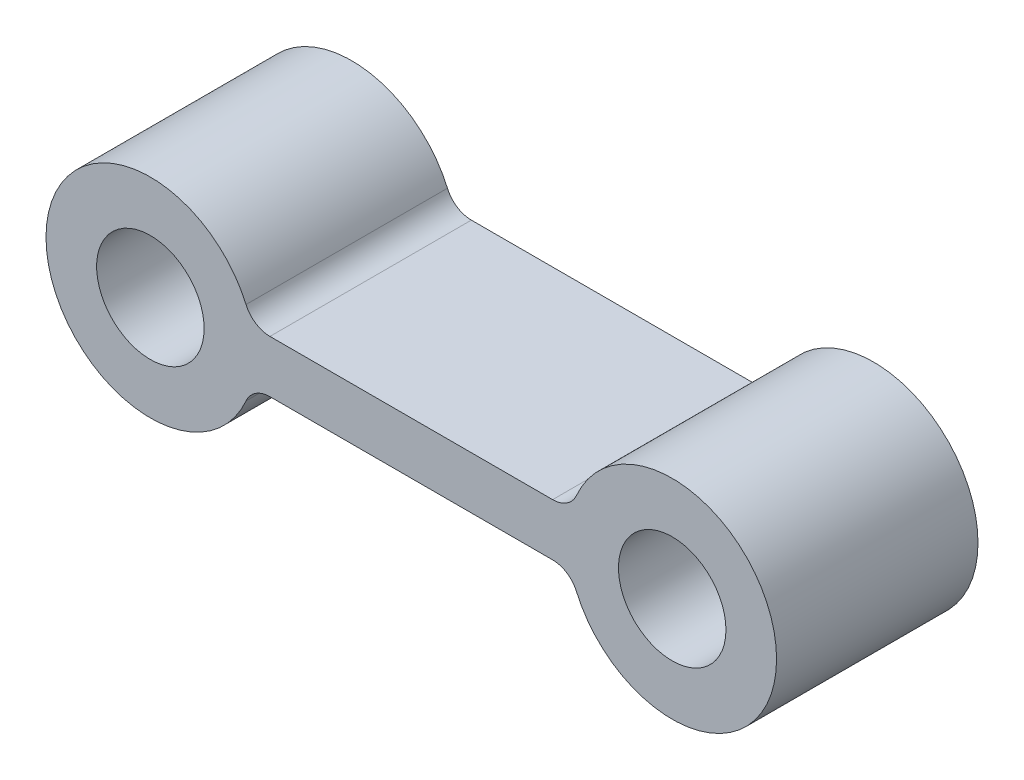
SolidWorks part; units mm, degrees
ref_plane "front" through (0, 0, 0) normal (0, 0, 1) x (1, 0, 0)
ref_plane "top" through (0, 0, 0) normal (0, 1, 0) x (1, 0, 0)
ref_plane "right" through (0, 0, 0) normal (1, 0, 0) x (0, 0, -1)
sketch "Sketch1" plane through (0, 0, 0) normal (0, 0, 1) x (1, 0, 0)
  line L0 (17.2003, 3.175) -> (-17.2003, 3.175)
  line L1 (17.2003, -3.175) -> (-17.2003, -3.175)
  circle A0 centre (31.75, 0) radius 6.5405
  circle A1 centre (-31.75, 0) radius 6.5405
  arc A2 (20.1103, -5.08) -> (20.1103, 5.08) centre (31.75, 0) ccw
  arc A3 (-20.1103, 5.08) -> (-20.1103, -5.08) centre (-31.75, 0) ccw
  arc A4 (17.2003, -3.175) -> (20.1103, -5.08) centre (17.2003, -6.35) cw
  arc A5 (17.2003, 3.175) -> (20.1103, 5.08) centre (17.2003, 6.35) ccw
  arc A6 (-17.2003, 3.175) -> (-20.1103, 5.08) centre (-17.2003, 6.35) cw
  arc A7 (-17.2003, -3.175) -> (-20.1103, -5.08) centre (-17.2003, -6.35) ccw
  point P17 (44.45, 0)
  point P18 (-44.45, 0)
  dimension "D1" = 13.081
  dimension "D6" = 12.7
  dimension "D7" = 3.175
  dimension "D2" = 31.75
  dimension "D3" = 63.5
  dimension "D4" = 3.175
  dimension "D5" = 6.35
  dimension "D8" = 88.9
  dimension "D9" = 17.2003
  dimension "D10" = 20.1103
  dimension "D11" = 5.08
  dimension "D12" = 17.2003
  dimension "D13" = 6.35
extrude "Base-Extrude" add sketch "Sketch1" along normal blind 24.511
sketch "Sketch2" plane through (0, 0, 0) normal (0, 0, 1) x (1, 0, 0)
  line L0 (121.9753, 3.175) -> (87.5747, 3.175)
  line L1 (154.0002, 165.1) -> (-49.1998, 165.1)
  line L2 (154.0002, 165.1) -> (154.0002, -12.7)
  line L3 (154.0002, -12.7) -> (-49.1998, -12.7)
  line L4 (-49.1998, 165.1) -> (-49.1998, -12.7)
  line L5 (87.5747, -3.175) -> (121.9753, -3.175)
  line L6 (17.2003, 3.175) -> (-17.2003, 3.175)
  line L7 (-17.2003, -3.175) -> (17.2003, -3.175)
  line L8 (17.2003, 3.175) -> (-17.2003, 3.175)
  line L9 (-17.2003, -3.175) -> (17.2003, -3.175)
  line L10 (17.2003, 53.975) -> (-17.2003, 53.975)
  line L11 (-17.2003, 47.625) -> (17.2003, 47.625)
  line L12 (121.9753, 53.975) -> (87.5747, 53.975)
  line L13 (87.5747, 47.625) -> (121.9753, 47.625)
  line L14 (17.2003, 104.775) -> (-17.2003, 104.775)
  line L15 (-17.2003, 98.425) -> (17.2003, 98.425)
  line L16 (121.9753, 104.775) -> (87.5747, 104.775)
  line L17 (87.5747, 98.425) -> (121.9753, 98.425)
  line L18 (17.2003, 155.575) -> (-17.2003, 155.575)
  line L19 (-17.2003, 149.225) -> (17.2003, 149.225)
  line L20 (121.9753, 155.575) -> (87.5747, 155.575)
  line L21 (87.5747, 149.225) -> (121.9753, 149.225)
  line L22 (17.2003, 3.175) -> (121.9753, 3.175) construction
  line L23 (17.2003, 3.175) -> (17.2003, 53.975) construction
  line L24 (60.325, 0) -> (44.45, 0) construction
  arc A0 (124.8853, -5.08) -> (121.9753, -3.175) centre (121.9753, -6.35) ccw
  arc A1 (124.8853, -5.08) -> (124.8853, 5.08) centre (136.525, 0) ccw
  arc A2 (121.9753, 3.175) -> (124.8853, 5.08) centre (121.9753, 6.35) ccw
  arc A3 (84.6647, 5.08) -> (87.5747, 3.175) centre (87.5747, 6.35) ccw
  arc A4 (84.6647, 5.08) -> (84.6647, -5.08) centre (73.025, 0) ccw
  arc A5 (87.5747, -3.175) -> (84.6647, -5.08) centre (87.5747, -6.35) ccw
  arc A6 (20.1103, -5.08) -> (17.2003, -3.175) centre (17.2003, -6.35) ccw
  arc A7 (20.1103, -5.08) -> (20.1103, 5.08) centre (31.75, 0) ccw
  arc A8 (17.2003, 3.175) -> (20.1103, 5.08) centre (17.2003, 6.35) ccw
  arc A9 (-20.1103, 5.08) -> (-17.2003, 3.175) centre (-17.2003, 6.35) ccw
  arc A10 (-20.1103, 5.08) -> (-20.1103, -5.08) centre (-31.75, 0) ccw
  arc A11 (-17.2003, -3.175) -> (-20.1103, -5.08) centre (-17.2003, -6.35) ccw
  arc A12 (20.1103, -5.08) -> (17.2003, -3.175) centre (17.2003, -6.35) ccw
  arc A13 (20.1103, -5.08) -> (20.1103, 5.08) centre (31.75, 0) ccw
  arc A14 (17.2003, 3.175) -> (20.1103, 5.08) centre (17.2003, 6.35) ccw
  arc A15 (-20.1103, 5.08) -> (-17.2003, 3.175) centre (-17.2003, 6.35) ccw
  arc A16 (-20.1103, 5.08) -> (-20.1103, -5.08) centre (-31.75, 0) ccw
  arc A17 (-17.2003, -3.175) -> (-20.1103, -5.08) centre (-17.2003, -6.35) ccw
  arc A18 (20.1103, 45.72) -> (17.2003, 47.625) centre (17.2003, 44.45) ccw
  arc A19 (20.1103, 45.72) -> (20.1103, 55.88) centre (31.75, 50.8) ccw
  arc A20 (17.2003, 53.975) -> (20.1103, 55.88) centre (17.2003, 57.15) ccw
  arc A21 (-20.1103, 55.88) -> (-17.2003, 53.975) centre (-17.2003, 57.15) ccw
  arc A22 (-20.1103, 55.88) -> (-20.1103, 45.72) centre (-31.75, 50.8) ccw
  arc A23 (-17.2003, 47.625) -> (-20.1103, 45.72) centre (-17.2003, 44.45) ccw
  arc A24 (124.8853, 45.72) -> (121.9753, 47.625) centre (121.9753, 44.45) ccw
  arc A25 (124.8853, 45.72) -> (124.8853, 55.88) centre (136.525, 50.8) ccw
  arc A26 (121.9753, 53.975) -> (124.8853, 55.88) centre (121.9753, 57.15) ccw
  arc A27 (84.6647, 55.88) -> (87.5747, 53.975) centre (87.5747, 57.15) ccw
  arc A28 (84.6647, 55.88) -> (84.6647, 45.72) centre (73.025, 50.8) ccw
  arc A29 (87.5747, 47.625) -> (84.6647, 45.72) centre (87.5747, 44.45) ccw
  arc A30 (20.1103, 96.52) -> (17.2003, 98.425) centre (17.2003, 95.25) ccw
  arc A31 (20.1103, 96.52) -> (20.1103, 106.68) centre (31.75, 101.6) ccw
  arc A32 (17.2003, 104.775) -> (20.1103, 106.68) centre (17.2003, 107.95) ccw
  arc A33 (-20.1103, 106.68) -> (-17.2003, 104.775) centre (-17.2003, 107.95) ccw
  arc A34 (-20.1103, 106.68) -> (-20.1103, 96.52) centre (-31.75, 101.6) ccw
  arc A35 (-17.2003, 98.425) -> (-20.1103, 96.52) centre (-17.2003, 95.25) ccw
  arc A36 (124.8853, 96.52) -> (121.9753, 98.425) centre (121.9753, 95.25) ccw
  arc A37 (124.8853, 96.52) -> (124.8853, 106.68) centre (136.525, 101.6) ccw
  arc A38 (121.9753, 104.775) -> (124.8853, 106.68) centre (121.9753, 107.95) ccw
  arc A39 (84.6647, 106.68) -> (87.5747, 104.775) centre (87.5747, 107.95) ccw
  arc A40 (84.6647, 106.68) -> (84.6647, 96.52) centre (73.025, 101.6) ccw
  arc A41 (87.5747, 98.425) -> (84.6647, 96.52) centre (87.5747, 95.25) ccw
  arc A42 (20.1103, 147.32) -> (17.2003, 149.225) centre (17.2003, 146.05) ccw
  arc A43 (20.1103, 147.32) -> (20.1103, 157.48) centre (31.75, 152.4) ccw
  arc A44 (17.2003, 155.575) -> (20.1103, 157.48) centre (17.2003, 158.75) ccw
  arc A45 (-20.1103, 157.48) -> (-17.2003, 155.575) centre (-17.2003, 158.75) ccw
  arc A46 (-20.1103, 157.48) -> (-20.1103, 147.32) centre (-31.75, 152.4) ccw
  arc A47 (-17.2003, 149.225) -> (-20.1103, 147.32) centre (-17.2003, 146.05) ccw
  arc A48 (124.8853, 147.32) -> (121.9753, 149.225) centre (121.9753, 146.05) ccw
  arc A49 (124.8853, 147.32) -> (124.8853, 157.48) centre (136.525, 152.4) ccw
  arc A50 (121.9753, 155.575) -> (124.8853, 157.48) centre (121.9753, 158.75) ccw
  arc A51 (84.6647, 157.48) -> (87.5747, 155.575) centre (87.5747, 158.75) ccw
  arc A52 (84.6647, 157.48) -> (84.6647, 147.32) centre (73.025, 152.4) ccw
  arc A53 (87.5747, 149.225) -> (84.6647, 147.32) centre (87.5747, 146.05) ccw
  dimension "D5" = 41.275
  dimension "D6" = 50.8
  dimension "D7" = 12.7
  dimension "D8" = 12.7
  dimension "D9" = 17.4752
  dimension "D10" = 17.4498
  dimension "D1" = 203.2
  dimension "D2" = 177.8
  dimension "D4" = 90
  dimension "D11" = 15.875
  dimension "D3" = 0
